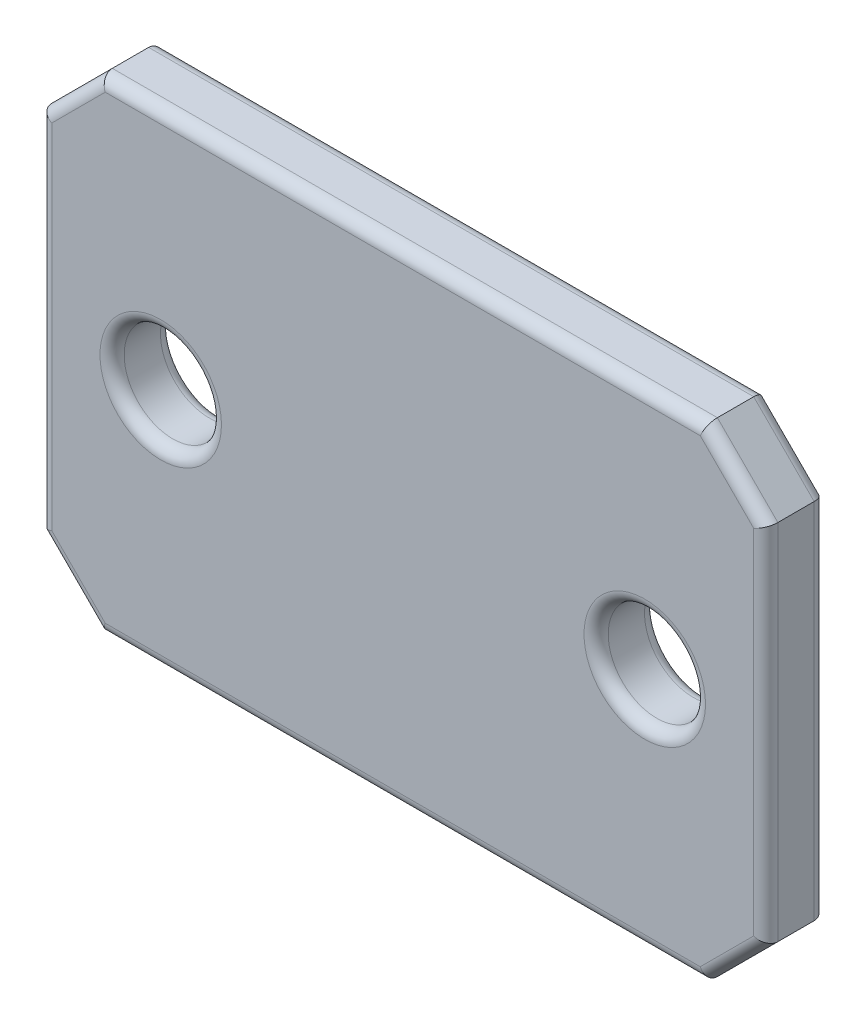
SolidWorks part; units mm, degrees
ref_plane "Front" through (0, 0, 0) normal (0, 0, 1) x (1, 0, 0)
ref_plane "Top" through (0, 0, 0) normal (0, 1, 0) x (1, 0, 0)
ref_plane "Right" through (0, 0, 0) normal (1, 0, 0) x (0, 0, -1)
sketch "Sketch1" plane through (0, 0, 0) normal (0, 0, 1) x (1, 0, 0)
  line L8 (15.875, 12.7) -> (-15.875, 12.7)
  line L10 (-19.05, 9.525) -> (-19.05, -9.525)
  line L12 (-15.875, -12.7) -> (15.875, -12.7)
  line L14 (19.05, -9.525) -> (19.05, 9.525)
  line L24 (15.875, 12.7) -> (-15.875, 12.7)
  line L26 (-19.05, 9.525) -> (-19.05, -9.525)
  line L28 (-15.875, -12.7) -> (15.875, -12.7)
  line L30 (19.05, -9.525) -> (19.05, 9.525)
  line L92 (-15.875, 12.7) -> (-19.05, 9.525)
  line L93 (-15.875, 12.7) -> (-19.05, 9.525)
  line L94 (-19.05, -9.525) -> (-15.875, -12.7)
  line L95 (-19.05, -9.525) -> (-15.875, -12.7)
  line L96 (15.875, -12.7) -> (19.05, -9.525)
  line L97 (15.875, -12.7) -> (19.05, -9.525)
  line L98 (19.05, 9.525) -> (15.875, 12.7)
  line L99 (19.05, 9.525) -> (15.875, 12.7)
  dimension "D1" = 0
extrude "Boss-Extrude1" add sketch "Sketch1" along normal blind 3.175
hole_wizard "#10 Clearance Hole1" positions "Sketch2" profile "Sketch3" hole size "#10" standard "ANSI Inch" end condition through all
sketch "Sketch2" plane through (0, 0, 3.175) normal (0, 0, 1) x (1, 0, 0)
  circle A0 centre (12.7, 0) radius 2.5527 construction
  circle A1 centre (-12.7, 0) radius 2.5527 construction
  point P2 (12.7, 0)
  point P4 (-12.7, 0)
  point P22 (12.7279, 0)
sketch "Sketch3" plane through (12.7, 0, 3.175) normal (1, 0, 0) x (0, -1, 0)
  line L0 (0, 0) -> (0, 3.175)
  line L1 (0, 3.175) -> (2.5527, 3.175)
  line L2 (2.5527, 3.175) -> (2.5527, 0)
  line L5 (2.5527, 0) -> (0, 0)
  line L11 (0, -6.35) -> (0, 107.95) construction
  dimension "Thru Hole Dia." = 5.1054
  dimension "Thru Hole Depth" = 3.175
fillet "Fillet1" radius 0.635 20 edges at (17.4625, 11.1125, 3.175) (-10.1473, 0, 3.175) (15.2527, 0, 3.175) (17.4625, 11.1125, 0) (-10.1473, 0, 0) (15.2527, 0, 0) (0, 12.7, 0) (-17.4625, 11.1125, 0) (-19.05, 0, 0) (-17.4625, -11.1125, 0) (0, -12.7, 0) (17.4625, -11.1125, 0) (19.05, 0, 0) (19.05, 0, 3.175) (17.4625, -11.1125, 3.175) (0, -12.7, 3.175) (-17.4625, -11.1125, 3.175) (-19.05, 0, 3.175) (-17.4625, 11.1125, 3.175) (0, 12.7, 3.175)
